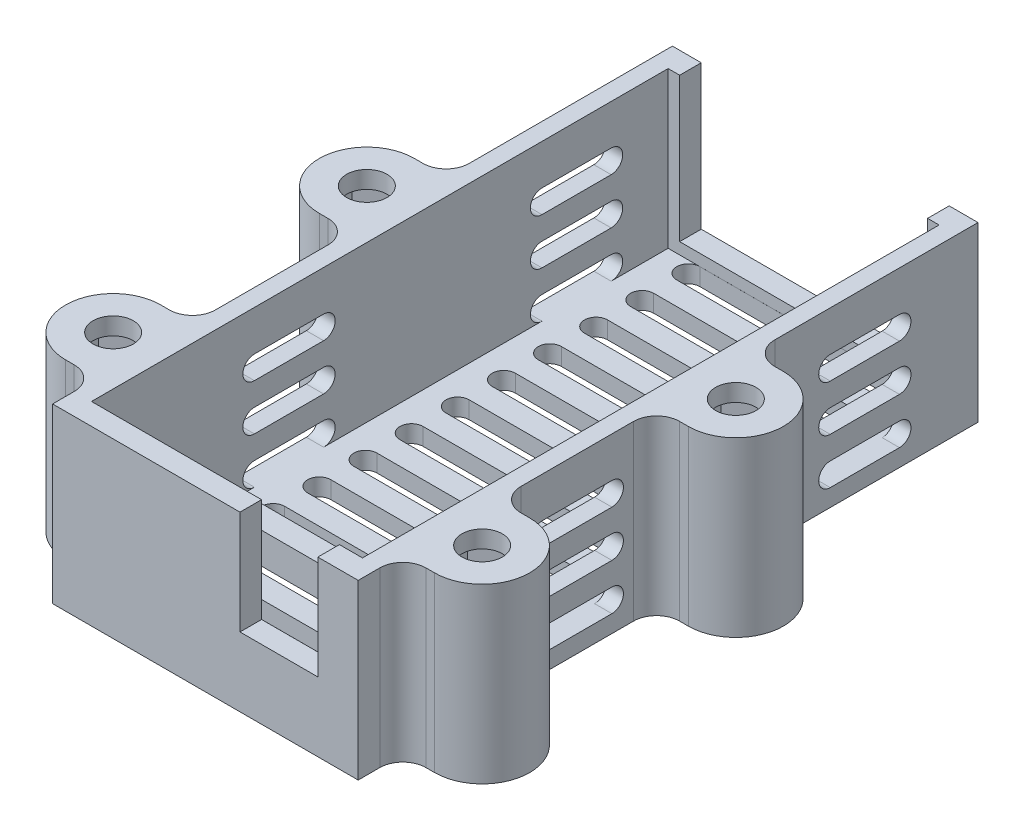
SolidWorks part; units mm, degrees
ref_plane "Front Plane" through (0, 0, 0) normal (0, 0, 1) x (1, 0, 0)
ref_plane "Top Plane" through (0, 0, 0) normal (0, 1, 0) x (1, 0, 0)
ref_plane "Right Plane" through (0, 0, 0) normal (1, 0, 0) x (0, 0, -1)
sketch "Sketch1" plane through (0, 0, 0) normal (0, 1, 0) x (1, 0, 0)
  line L0 (0, 26.875) -> (0, -26.875) construction
  line L1 (-11.75, 25.375) -> (11.75, 25.375)
  line L2 (-11.75, 25.375) -> (-11.75, -25.375)
  line L3 (-11.75, -25.375) -> (11.75, -25.375)
  line L4 (11.75, 25.375) -> (11.75, -25.375)
  line L5 (-11.75, 25.375) -> (11.75, -25.375) construction
  line L6 (-11.75, -25.375) -> (11.75, 25.375) construction
  line L7 (13.25, 26.875) -> (-13.25, 26.875)
  line L8 (13.25, 26.875) -> (13.25, -26.875)
  line L9 (13.25, -26.875) -> (-13.25, -26.875)
  line L10 (-13.25, 26.875) -> (-13.25, -26.875)
  line L11 (13.25, 26.875) -> (-13.25, -26.875) construction
  line L12 (13.25, -26.875) -> (-13.25, 26.875) construction
  line L13 (-16, -14.75) -> (-13.25, -14.75)
  line L14 (-16, -23) -> (-13.25, -23)
  line L15 (-16, -1) -> (-13.25, -1)
  line L16 (-16, 7.25) -> (-13.25, 7.25)
  line L17 (16, -23) -> (13.25, -23)
  line L18 (16, -14.75) -> (13.25, -14.75)
  line L19 (16, -1) -> (13.25, -1)
  line L20 (16, 7.25) -> (13.25, 7.25)
  circle A0 centre (-16, -18.875) radius 1.75
  circle A1 centre (-16, -18.875) radius 4.125
  circle A2 centre (-16, 3.125) radius 1.75
  circle A3 centre (-16, 3.125) radius 4.125
  circle A4 centre (16, -18.875) radius 1.75
  circle A5 centre (16, -18.875) radius 4.125
  circle A6 centre (16, 3.125) radius 1.75
  circle A7 centre (16, 3.125) radius 4.125
  point P0 (0, 0)
  point P6 (0, 0)
  dimension "D5" = 8.25
  dimension "D6" = 3.5
  dimension "D1" = 23.5
  dimension "D2" = 50.75
  dimension "D3" = 1.5
  dimension "D4" = 1.5
  dimension "D7" = 32
  dimension "D8" = 6.5
  dimension "D10" = 22
  dimension "D9" = 2
extrude "Boss-Extrude2" add sketch "Sketch1" along normal blind 1.5 contours L4 L1 L2 L3 | L8 A7 L7 L10 A3 A1 L9 A5 L1 L4 L3 L2 | L10 A3 | L10 A1 | A5 L8 | A7 L8 | L19 A7 L8 | A7 L8 A6 | L8 A7 L20 | L8 A5 L18 | A5 L8 A4 | L17 A5 L8 | A1 L10 L13 | A1 L10 A0 | A1 L14 L10 | A3 L10 L16 | A3 L10 A2 | A3 L15 L10
sketch "Sketch2" plane through (0, 1.5, 0) normal (0, 1, 0) x (1, 0, 0)
  line L1 (11.75, 25.0026) -> (-11.75, 25.0026)
  line L2 (11.75, 25.0026) -> (11.75, -25.0026)
  line L3 (11.75, -25.0026) -> (-11.75, -25.0026)
  line L4 (-11.75, 25.0026) -> (-11.75, -25.0026)
  line L5 (11.75, 25.0026) -> (-11.75, -25.0026) construction
  line L6 (11.75, -25.0026) -> (-11.75, 25.0026) construction
  line L16 (16, -14.75) -> (13.25, -14.75)
  line L17 (13.25, -14.75) -> (13.25, -1)
  line L18 (13.25, -1) -> (16, -1)
  line L19 (16, 7.25) -> (13.25, 7.25)
  line L20 (13.25, 7.25) -> (13.25, 26.875)
  line L21 (13.25, 26.875) -> (-13.25, 26.875)
  line L22 (13.25, 26.875) -> (-13.25, 26.875)
  line L23 (-13.25, 26.875) -> (-13.25, 7.25)
  line L24 (-13.25, 26.875) -> (-13.25, 7.25)
  line L25 (-13.25, 7.25) -> (-16, 7.25)
  line L26 (-13.25, 7.25) -> (-16, 7.25)
  line L27 (-16, -1) -> (-13.25, -1)
  line L28 (-16, -1) -> (-13.25, -1)
  line L29 (-13.25, -1) -> (-13.25, -14.75)
  line L30 (13.25, -26.875) -> (13.25, -23)
  line L31 (13.25, -23) -> (16, -23)
  line L32 (16, -14.75) -> (13.25, -14.75)
  line L33 (13.25, -14.75) -> (13.25, -1)
  line L34 (13.25, -1) -> (16, -1)
  line L35 (16, 7.25) -> (13.25, 7.25)
  line L36 (13.25, 7.25) -> (13.25, 26.875)
  line L37 (-13.25, -1) -> (-13.25, -14.75)
  line L44 (-13.25, -14.75) -> (-16, -14.75)
  line L45 (-13.25, -14.75) -> (-16, -14.75)
  line L46 (13.25, -26.875) -> (13.25, -23)
  line L47 (13.25, -23) -> (16, -23)
  line L48 (-16, -23) -> (-13.25, -23)
  line L49 (-16, -23) -> (-13.25, -23)
  line L50 (-13.25, -23) -> (-13.25, -26.875)
  line L51 (-13.25, -23) -> (-13.25, -26.875)
  line L52 (-13.25, -26.875) -> (13.25, -26.875)
  line L53 (-13.25, -26.875) -> (13.25, -26.875)
  circle A0 centre (-16, 3.125) radius 1.75 construction
  circle A1 centre (-16, -18.875) radius 1.75 construction
  circle A2 centre (16, -18.875) radius 1.75 construction
  circle A3 centre (16, 3.125) radius 1.75 construction
  arc A4 (16, -23) -> (16, -14.75) centre (16, -18.875) ccw
  arc A5 (16, -1) -> (16, 7.25) centre (16, 3.125) ccw
  arc A6 (-16, 7.25) -> (-16, -1) centre (-16, 3.125) ccw
  arc A7 (-16, 7.25) -> (-16, -1) centre (-16, 3.125) ccw
  arc A8 (16, -23) -> (16, -14.75) centre (16, -18.875) ccw
  arc A9 (16, -1) -> (16, 7.25) centre (16, 3.125) ccw
  arc A10 (-16, -14.75) -> (-16, -23) centre (-16, -18.875) ccw
  arc A11 (-16, -14.75) -> (-16, -23) centre (-16, -18.875) ccw
  circle A12 centre (-16, 3.125) radius 1.75
  circle A13 centre (-16, -18.875) radius 1.75
  circle A14 centre (16, -18.875) radius 1.75
  circle A15 centre (16, 3.125) radius 1.75
  point P0 (0, 0)
  dimension "D3" = 1.5
  dimension "D1" = 0
extrude "Boss-Extrude3" add sketch "Sketch2" along normal blind 13.5
sketch "Sketch3" plane through (0, 15, 0) normal (0, 1, 0) x (1, 0, 0)
  line L0 (13.25, 26.875) -> (-13.25, 26.875) construction
  line L1 (-10.75, 26.875) -> (10.75, 26.875)
  line L2 (-10.75, 26.875) -> (-10.75, 25.0026)
  line L3 (-10.75, 25.0026) -> (10.75, 25.0026)
  line L4 (10.75, 26.875) -> (10.75, 25.0026)
  line L5 (11.75, 25.0026) -> (-11.75, 25.0026) construction
  line L6 (-11.75, 25.0026) -> (-11.75, -25.0026) construction
  line L7 (11.75, -25.0026) -> (11.75, 25.0026) construction
  dimension "D1" = 1
  dimension "D2" = 1
extrude "Cut-Extrude1" cut sketch "Sketch3" against normal offset from surface (12.5 mm away) 1
sketch "Sketch4" plane through (0, 0, 26.875) normal (0, 0, 1) x (1, 0, 0)
  line L0 (11.75, 15) -> (11.75, 0) construction
  line L1 (-13.25, 15) -> (13.25, 15) construction
  line L2 (13.25, 0) -> (-13.25, 0) construction
  line L3 (-11.75, 15) -> (-11.75, 0) construction
  line L4 (11.75, 1.5) -> (-11.75, 1.5) construction
  line L5 (9.75, 6) -> (3, 6)
  line L6 (9.75, 6) -> (9.75, 15)
  line L7 (9.75, 15) -> (3, 15)
  line L8 (3, 6) -> (3, 15)
  line L9 (-13.25, 1.5) -> (13.25, 1.5) construction
  line L10 (-13.25, 15) -> (-13.25, 0) construction
  line L11 (13.25, 15) -> (13.25, 0) construction
  line L12 (0, 15) -> (0, 0) construction
  line M3 (13.25, 15) -> (-13.25, 15)
  dimension "D1" = 2
  dimension "D2" = 6.75
  dimension "D3" = 4.5
extrude "Cut-Extrude2" cut sketch "Sketch4" against normal up to next contours L8 L5 L6 M3
sketch "Sketch5" plane through (0, 0, 0) normal (0, -1, 0) x (1, 0, 0)
  line L1 (-16, 15.4109) -> (-13, 17.1429)
  line L2 (-13, 17.1429) -> (-13, 20.6071)
  line L3 (-13, 20.6071) -> (-16, 22.3391)
  line L4 (-16, 22.3391) -> (-19, 20.6071)
  line L5 (-19, 20.6071) -> (-19, 17.1429)
  line L6 (-19, 17.1429) -> (-16, 15.4109)
  line L7 (16, 15.4109) -> (19, 17.1429)
  line L8 (19, 17.1429) -> (19, 20.6071)
  line L9 (19, 20.6071) -> (16, 22.3391)
  line L10 (16, 22.3391) -> (13, 20.6071)
  line L11 (13, 20.6071) -> (13, 17.1429)
  line L12 (13, 17.1429) -> (16, 15.4109)
  line L13 (16, -6.5891) -> (19, -4.8571)
  line L14 (19, -4.8571) -> (19, -1.3929)
  line L15 (19, -1.3929) -> (16, 0.3391)
  line L16 (16, 0.3391) -> (13, -1.3929)
  line L17 (13, -1.3929) -> (13, -4.8571)
  line L18 (13, -4.8571) -> (16, -6.5891)
  line L19 (-16, -6.5891) -> (-13, -4.8571)
  line L20 (-13, -4.8571) -> (-13, -1.3929)
  line L21 (-13, -1.3929) -> (-16, 0.3391)
  line L22 (-16, 0.3391) -> (-19, -1.3929)
  line L23 (-19, -1.3929) -> (-19, -4.8571)
  line L24 (-19, -4.8571) -> (-16, -6.5891)
  circle A0 centre (-16, 18.875) radius 3 construction
  circle A1 centre (16, 18.875) radius 3 construction
  circle A2 centre (16, -3.125) radius 3 construction
  circle A3 centre (-16, -3.125) radius 3 construction
  dimension "D1" = 6
extrude "Cut-Extrude3" cut sketch "Sketch5" against normal offset from surface (13.5 mm away) 1.5 up to face at (-16, 15, -1.375)
sketch "Sketch6" plane through (0, 0, 0) normal (0, -1, 0) x (1, 0, 0)
  line L0 (0, 26.875) -> (0, -26.875) construction
  line L1 (13.25, 26.875) -> (-13.25, 26.875) construction
  line L2 (13.25, -26.875) -> (-13.25, -26.875) construction
  line L3 (-9, 0) -> (9, 0) construction
  line L4 (-9, 1) -> (9, 1)
  line L5 (-9, -1) -> (9, -1)
  line L6 (-9, 4) -> (9, 4) construction
  line L7 (-9, 5) -> (9, 5)
  line L8 (-9, 3) -> (9, 3)
  line L9 (-9, 8) -> (9, 8) construction
  line L10 (-9, 9) -> (9, 9)
  line L11 (-9, 7) -> (9, 7)
  line L12 (-9, 12) -> (9, 12) construction
  line L13 (-9, 13) -> (9, 13)
  line L14 (-9, 11) -> (9, 11)
  line L15 (-9, 16) -> (9, 16) construction
  line L16 (-9, 17) -> (9, 17)
  line L17 (-9, 15) -> (9, 15)
  line L18 (-9, 20) -> (9, 20) construction
  line L19 (-9, 21) -> (9, 21)
  line L20 (-9, 19) -> (9, 19)
  line L21 (-9, 24) -> (9, 24) construction
  line L22 (-9, 25) -> (9, 25)
  line L23 (-9, 23) -> (9, 23)
  line L24 (-13.25, 0) -> (13.25, 0) construction
  line L25 (-13.25, -26.875) -> (-13.25, -7.25) construction
  line L26 (13.25, -26.875) -> (13.25, -7.25) construction
  line L27 (-9, -4) -> (9, -4) construction
  line L28 (-9, -5) -> (9, -5)
  line L29 (-9, -3) -> (9, -3)
  line L30 (-9, -8) -> (9, -8) construction
  line L31 (-9, -9) -> (9, -9)
  line L32 (-9, -7) -> (9, -7)
  line L33 (-9, -12) -> (9, -12) construction
  line L34 (-9, -13) -> (9, -13)
  line L35 (-9, -11) -> (9, -11)
  line L36 (-9, -16) -> (9, -16) construction
  line L37 (-9, -17) -> (9, -17)
  line L38 (-9, -15) -> (9, -15)
  line L39 (-9, -20) -> (9, -20) construction
  line L40 (-9, -21) -> (9, -21)
  line L41 (-9, -19) -> (9, -19)
  line L42 (-9, -24) -> (9, -24) construction
  line L43 (-9, -25) -> (9, -25)
  line L44 (-9, -23) -> (9, -23)
  arc A0 (-9, 1) -> (-9, -1) centre (-9, 0) ccw
  arc A1 (9, -1) -> (9, 1) centre (9, 0) ccw
  arc A2 (-9, 5) -> (-9, 3) centre (-9, 4) ccw
  arc A3 (9, 3) -> (9, 5) centre (9, 4) ccw
  arc A4 (-9, 9) -> (-9, 7) centre (-9, 8) ccw
  arc A5 (9, 7) -> (9, 9) centre (9, 8) ccw
  arc A6 (-9, 13) -> (-9, 11) centre (-9, 12) ccw
  arc A7 (9, 11) -> (9, 13) centre (9, 12) ccw
  arc A8 (-9, 17) -> (-9, 15) centre (-9, 16) ccw
  arc A9 (9, 15) -> (9, 17) centre (9, 16) ccw
  arc A10 (-9, 21) -> (-9, 19) centre (-9, 20) ccw
  arc A11 (9, 19) -> (9, 21) centre (9, 20) ccw
  arc A12 (-9, 25) -> (-9, 23) centre (-9, 24) ccw
  arc A13 (9, 23) -> (9, 25) centre (9, 24) ccw
  arc A14 (-9, -5) -> (-9, -3) centre (-9, -4) cw
  arc A15 (9, -3) -> (9, -5) centre (9, -4) cw
  arc A16 (-9, -9) -> (-9, -7) centre (-9, -8) cw
  arc A17 (9, -7) -> (9, -9) centre (9, -8) cw
  arc A18 (-9, -13) -> (-9, -11) centre (-9, -12) cw
  arc A19 (9, -11) -> (9, -13) centre (9, -12) cw
  arc A20 (-9, -17) -> (-9, -15) centre (-9, -16) cw
  arc A21 (9, -15) -> (9, -17) centre (9, -16) cw
  arc A22 (-9, -21) -> (-9, -19) centre (-9, -20) cw
  arc A23 (9, -19) -> (9, -21) centre (9, -20) cw
  arc A24 (-9, -25) -> (-9, -23) centre (-9, -24) cw
  arc A25 (9, -23) -> (9, -25) centre (9, -24) cw
  point P8 (0, 0)
  point P18 (0, 4)
  point P25 (0, 8)
  point P32 (0, 12)
  point P39 (0, 16)
  point P46 (0, 20)
  point P53 (0, 24)
  point P64 (0, -4)
  point P71 (0, -8)
  point P78 (0, -12)
  point P85 (0, -16)
  point P92 (0, -20)
  point P99 (0, -24)
  dimension "D1" = 18
  dimension "D2" = 2
  dimension "D4" = 4
  dimension "D3" = 7
extrude "Cut-Extrude4" cut sketch "Sketch6" against normal up to next
sketch "Sketch7" plane through (0, 1.5, 0) normal (0, 1, 0) x (1, 0, 0)
  line L0 (-11.75, 25.0026) -> (-11.75, -25.0026) construction
  line L1 (-11.75, -13) -> (11.75, -13)
  line L2 (-11.75, -13) -> (-11.75, -15)
  line L3 (-11.75, -15) -> (11.75, -15)
  line L4 (11.75, -13) -> (11.75, -15)
  line L7 (11.75, -25.0026) -> (11.75, 25.0026) construction
  line L9 (-9, -15) -> (9, -15) construction
  line L10 (9, -13) -> (-9, -13) construction
extrude "Boss-Extrude4" add sketch "Sketch7" along normal blind 1.2
sketch "Sketch8" plane through (13.25, 0, 0) normal (1, 0, 0) x (0, 0, -1)
  line L0 (-7.875, 15) -> (-7.875, 0) construction
  line L1 (-14.75, 15) -> (-1, 15) construction
  line L2 (-1, 0) -> (-14.75, 0) construction
  line L3 (17.0625, 15) -> (17.0625, 0) construction
  line L4 (7.25, 15) -> (26.875, 15) construction
  line L5 (26.875, 0) -> (7.25, 0) construction
  line L6 (-26.875, 2.5) -> (26.875, 2.5) construction
  line L7 (-26.875, 15) -> (-26.875, 0) construction
  line L8 (26.875, 15) -> (26.875, 0) construction
  line L9 (-10.875, 2.5) -> (-4.875, 2.5) construction
  line L10 (-10.875, 3.5) -> (-4.875, 3.5)
  line L11 (-10.875, 1.5) -> (-4.875, 1.5)
  line L12 (14.0625, 2.5) -> (20.0625, 2.5) construction
  line L13 (14.0625, 3.5) -> (20.0625, 3.5)
  line L14 (14.0625, 1.5) -> (20.0625, 1.5)
  line L17 (-10.875, 6.5) -> (-4.875, 6.5) construction
  line L18 (-10.875, 7.5) -> (-4.875, 7.5)
  line L19 (-10.875, 5.5) -> (-4.875, 5.5)
  line L20 (14.0625, 6.5) -> (20.0625, 6.5) construction
  line L21 (14.0625, 7.5) -> (20.0625, 7.5)
  line L22 (14.0625, 5.5) -> (20.0625, 5.5)
  line L23 (-10.875, 10.5) -> (-4.875, 10.5) construction
  line L24 (-10.875, 11.5) -> (-4.875, 11.5)
  line L25 (-10.875, 9.5) -> (-4.875, 9.5)
  line L26 (14.0625, 10.5) -> (20.0625, 10.5) construction
  line L27 (14.0625, 11.5) -> (20.0625, 11.5)
  line L28 (14.0625, 9.5) -> (20.0625, 9.5)
  arc A0 (-10.875, 3.5) -> (-10.875, 1.5) centre (-10.875, 2.5) ccw
  arc A1 (-4.875, 1.5) -> (-4.875, 3.5) centre (-4.875, 2.5) ccw
  arc A2 (14.0625, 3.5) -> (14.0625, 1.5) centre (14.0625, 2.5) ccw
  arc A3 (20.0625, 1.5) -> (20.0625, 3.5) centre (20.0625, 2.5) ccw
  arc A4 (-10.875, 7.5) -> (-10.875, 5.5) centre (-10.875, 6.5) ccw
  arc A5 (-4.875, 5.5) -> (-4.875, 7.5) centre (-4.875, 6.5) ccw
  arc A6 (14.0625, 7.5) -> (14.0625, 5.5) centre (14.0625, 6.5) ccw
  arc A7 (20.0625, 5.5) -> (20.0625, 7.5) centre (20.0625, 6.5) ccw
  arc A8 (-10.875, 11.5) -> (-10.875, 9.5) centre (-10.875, 10.5) ccw
  arc A9 (-4.875, 9.5) -> (-4.875, 11.5) centre (-4.875, 10.5) ccw
  arc A10 (14.0625, 11.5) -> (14.0625, 9.5) centre (14.0625, 10.5) ccw
  arc A11 (20.0625, 9.5) -> (20.0625, 11.5) centre (20.0625, 10.5) ccw
  point P20 (-7.875, 2.5)
  point P27 (17.0625, 2.5)
  point P39 (-7.875, 6.5)
  point P46 (17.0625, 6.5)
  point P53 (-7.875, 10.5)
  point P60 (17.0625, 10.5)
  dimension "D1" = 2.5
  dimension "D2" = 2
  dimension "D3" = 2
  dimension "D4" = 6
  dimension "D5" = 6
  dimension "D7" = 4
  dimension "D6" = 3
extrude "Cut-Extrude5" cut sketch "Sketch8" against normal up to surface (26.5 mm away) up to face at (-13.25, 7.5, -17.0625)
fillet "Fillet1" radius 2 8 edges at (-13.25, 7.5, 14.75) (-13.25, 7.5, 23) (-13.25, 7.5, 1) (-13.25, 7.5, -7.25) (13.25, 7.5, -7.25) (13.25, 7.5, 14.75) (13.25, 7.5, 23) (13.25, 7.5, 1)
